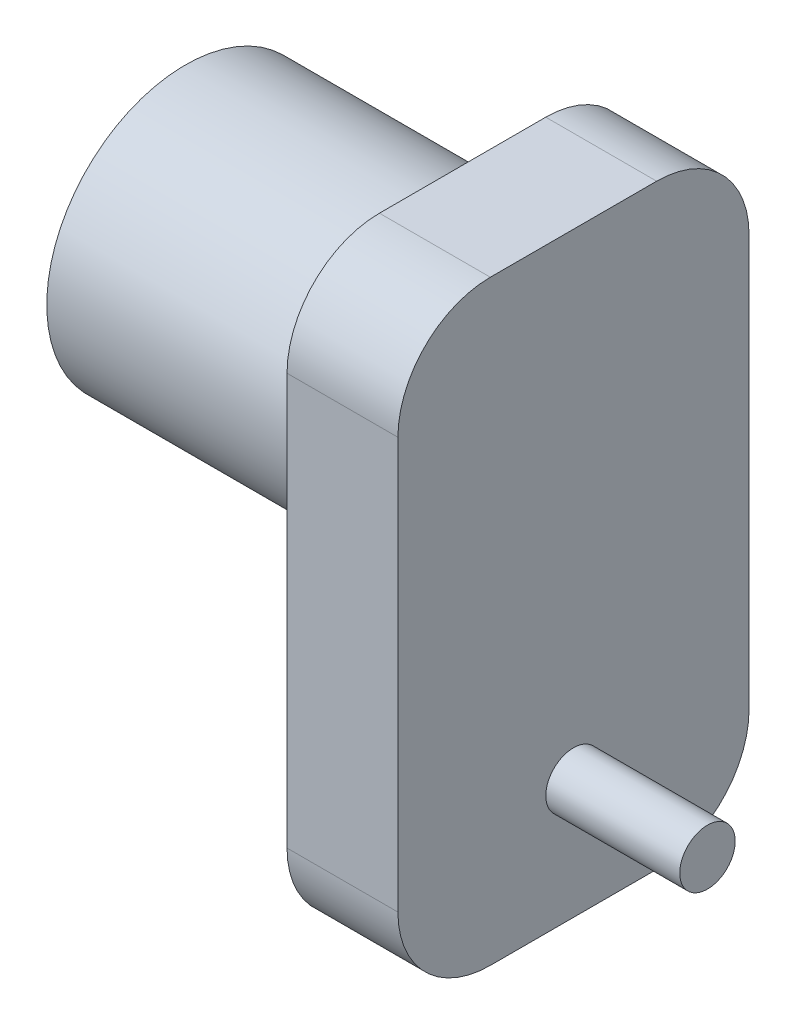
SolidWorks part; units mm, degrees
ref_plane "前视基准面" through (0, 0, 0) normal (0, 0, 1) x (1, 0, 0)
ref_plane "上视基准面" through (0, 0, 0) normal (0, 1, 0) x (1, 0, 0)
ref_plane "右视基准面" through (0, 0, 0) normal (1, 0, 0) x (0, 0, -1)
other "Configuration Table"
sketch "草图1" plane through (0, 0, 0) normal (1, 0, 0) x (0, 0, -1)
  line L1 (-19, 20.6) -> (19, 20.6)
  line L2 (-19, 20.6) -> (-19, -43.9)
  line L3 (-19, -43.9) -> (19, -43.9)
  line L4 (19, 20.6) -> (19, -43.9)
  circle A0 centre (0, 0) radius 15
  dimension "D1" = 30
  dimension "D2" = 38
  dimension "D4" = 20.6
  dimension "D3" = 64.5
  dimension "D5" = 19
extrude "凸台-拉伸1" add sketch "草图1" against normal blind 30 contours A0
sketch "草图8" plane through (0, 0, 0) normal (1, 0, 0) x (0, 0, -1)
  line L0 (19, 20.6) -> (19, -43.9) construction
  line L1 (19, 10.6) -> (19, -33.9)
  line L2 (-19, -43.9) -> (19, -43.9) construction
  line L3 (-19, 20.6) -> (-19, -43.9) construction
  line L4 (-19, 20.6) -> (19, 20.6) construction
  line L5 (-9, -43.9) -> (9, -43.9)
  line L6 (-19, 10.6) -> (-19, -33.9)
  line L7 (-9, 20.6) -> (9, 20.6)
  arc A0 (-9, 20.6) -> (-19, 10.6) centre (-9, 10.6) ccw
  circle A1 centre (0, 0) radius 15
  circle A2 centre (0, 0) radius 15
  arc A3 (19, -33.9) -> (9, -43.9) centre (9, -33.9) cw
  arc A4 (-9, -43.9) -> (-19, -33.9) centre (-9, -33.9) cw
  arc A5 (19, 10.6) -> (9, 20.6) centre (9, 10.6) ccw
  dimension "D2" = 10
  dimension "D3" = 10
  dimension "D1" = 0
extrude "凸台-拉伸2" add sketch "草图8" along normal blind 12 contours A0 L6 A4 L5 A3 L1 A5 L7
sketch "草图9" plane through (12, 0, 0) normal (1, 0, 0) x (0, 0, -1)
  line L0 (0, 0) -> (0, -31) construction
  circle A0 centre (0, -31) radius 3
  dimension "D2" = 6
  dimension "D1" = 31
extrude "凸台-拉伸3" add sketch "草图9" along normal blind 14.5
